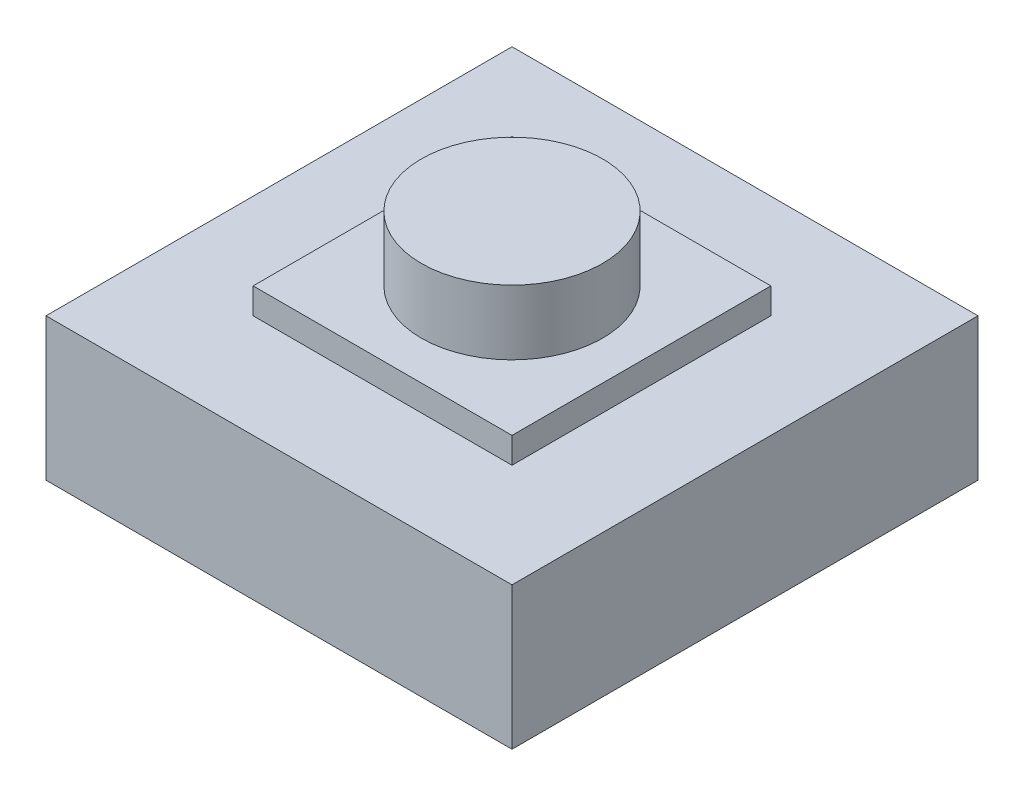
SolidWorks part; units mm, degrees
ref_plane "前视基准面" through (0, 0, 0) normal (0, 0, 1) x (1, 0, 0)
ref_plane "上视基准面" through (0, 0, 0) normal (0, 1, 0) x (1, 0, 0)
ref_plane "右视基准面" through (0, 0, 0) normal (1, 0, 0) x (0, 0, -1)
other "Configuration Table"
sketch "草图1" plane through (0, 0, 0) normal (0, 1, 0) x (1, 0, 0)
  line L1 (-18, -18) -> (18, -18)
  line L2 (-18, -18) -> (-18, 18)
  line L3 (-18, 18) -> (18, 18)
  line L4 (18, -18) -> (18, 18)
  line L5 (-18, -18) -> (18, 18) construction
  line L6 (-18, 18) -> (18, -18) construction
  point P0 (0, 0)
  dimension "D1" = 36
  dimension "D2" = 36
extrude "凸台-拉伸1" add sketch "草图1" along normal blind 11
sketch "草图2" plane through (0, 11, 0) normal (0, 1, 0) x (1, 0, 0)
  line L1 (10, 10) -> (-10, 10)
  line L2 (10, 10) -> (10, -10)
  line L3 (10, -10) -> (-10, -10)
  line L4 (-10, 10) -> (-10, -10)
  line L5 (10, 10) -> (-10, -10) construction
  line L6 (10, -10) -> (-10, 10) construction
  point P0 (0, 0)
  dimension "D1" = 20
  dimension "D2" = 20
extrude "凸台-拉伸2" add sketch "草图2" along normal blind 2
sketch "草图4" plane through (0, 13, 0) normal (0, 1, 0) x (1, 0, 0)
  circle A0 centre (0, 0) radius 7
  dimension "D1" = 14
extrude "凸台-拉伸4" add sketch "草图4" along normal blind 5
